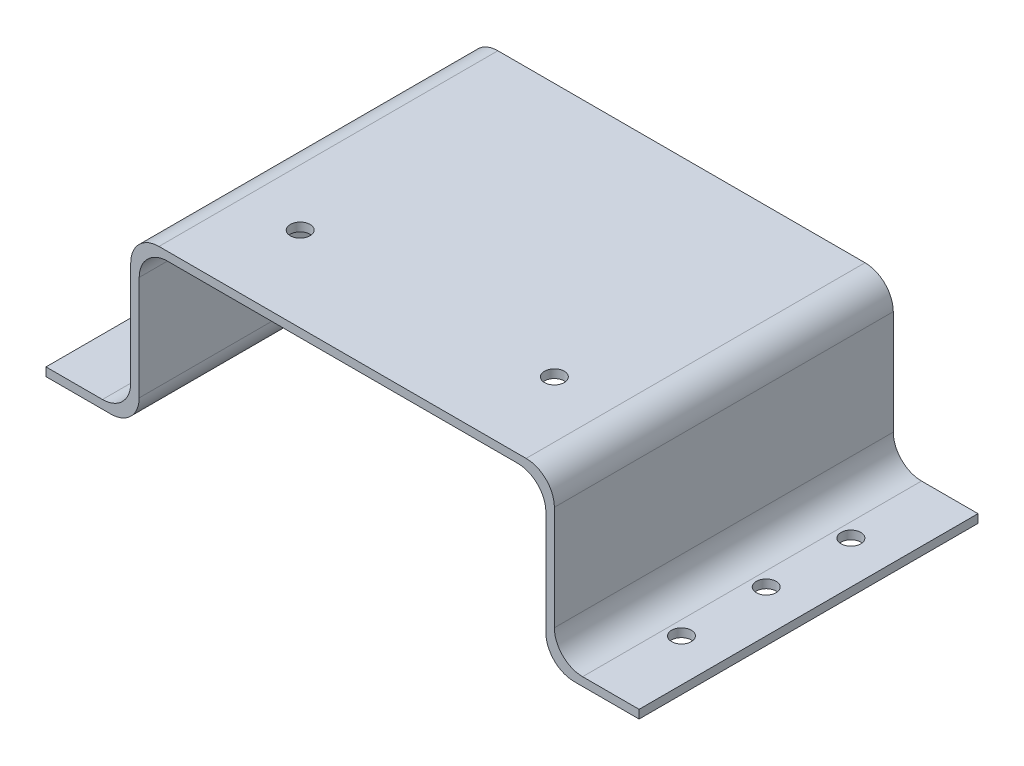
SolidWorks part; units mm, degrees
ref_plane "Front Plane" through (0, 0, 0) normal (0, 0, 1) x (1, 0, 0)
ref_plane "Top Plane" through (0, 0, 0) normal (0, 1, 0) x (1, 0, 0)
ref_plane "Right Plane" through (0, 0, 0) normal (1, 0, 0) x (0, 0, -1)
sketch "Sketch1" plane through (0, 0, 0) normal (0, 0, 1) x (1, 0, 0)
  line L0 (0, 0) -> (-150, 0)
  line L1 (0, 0) -> (0, -56.94)
  line L2 (-150, 0) -> (-150, -56.94)
  line L3 (0, -56.94) -> (30, -56.94)
  line L4 (-150, -56.94) -> (-180, -56.94)
  dimension "D1" = 150
  dimension "D2" = 56.94
  dimension "D3" = 30
  dimension "D4" = 30
extrude "Extrude-Thin1" add sketch "Sketch1" against normal blind 120 thin thin type one direction reverse wall 3
sketch "Sketch2" plane through (0, -56.94, 0) normal (0, 1, 0) x (1, 0, 0)
  line L0 (0, 0) -> (30, 0) construction
  line L1 (30, 0) -> (15, 0) construction
  line L2 (15, 0) -> (15, 120) construction
  line L3 (30, 120) -> (0, 120) construction
  line L5 (15, 0) -> (15, 30) construction
  line L8 (15, 120) -> (15, 90) construction
  line L9 (15, 90) -> (15, 60) construction
  line L10 (-75, 0) -> (-75, 120) construction
  line L11 (0, 0) -> (-150, 0) construction
  line L12 (0, 120) -> (-150, 120) construction
  circle A0 centre (15, 30) radius 3.5
  circle A1 centre (15, 60) radius 3.5
  circle A2 centre (15, 90) radius 3.5
  dimension "D1" = 30
  dimension "D2" = 7
  dimension "D4" = 7
  dimension "D5" = 7
  dimension "D3" = 30
extrude "Cut-Extrude1" cut sketch "Sketch2" against normal blind 10
pattern_linear "LPattern1" count 2 spacing 180 along (-1, 0, 0) of "Cut-Extrude1"
sketch "Sketch3" plane through (0, 0, 0) normal (0, 1, 0) x (1, 0, 0)
  line L0 (-75, 30) -> (-30, 30) construction
  line L1 (-75, 30) -> (-120, 30) construction
  line L3 (-75, 120) -> (-75, 0) construction
  line L4 (0, 120) -> (-150, 120) construction
  line L5 (0, 0) -> (-150, 0) construction
  circle A0 centre (-30, 30) radius 3.5
  circle A1 centre (-120, 30) radius 3.5
  dimension "D3" = 7
  dimension "D4" = 7
  dimension "D1" = 45
  dimension "D2" = 45
extrude "Cut-Extrude2" cut sketch "Sketch3" against normal blind 10
fillet "Fillet1" radius 10 8 edges at (-147, -59.94, -60) (-3, -59.94, -60) (-3, -3, -60) (-147, -3, -60) (-150, -56.94, -60) (0, -56.94, -60) (0, 0, -60) (-150, 0, -60)
